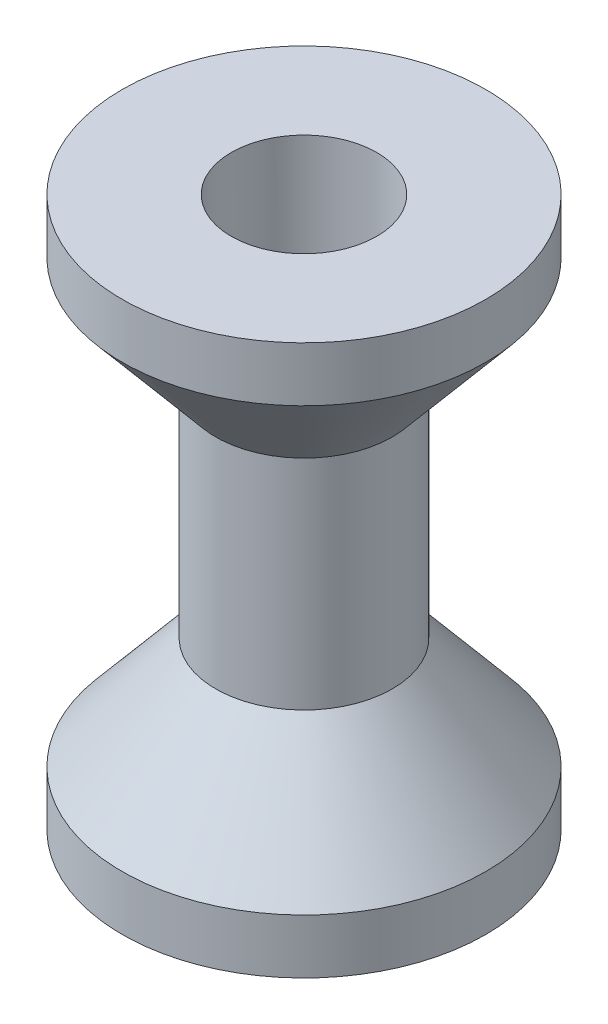
SolidWorks part; units mm, degrees
ref_plane "Alzado" through (0, 0, 0) normal (0, 0, 1) x (1, 0, 0)
ref_plane "Planta" through (0, 0, 0) normal (0, 1, 0) x (1, 0, 0)
ref_plane "Vista lateral" through (0, 0, 0) normal (1, 0, 0) x (0, 0, -1)
sketch "Croquis1" plane through (0, 0, 0) normal (0, 0, 1) x (1, 0, 0)
  line L0 (0, 6) -> (0, -6)
  line L1 (0, 0) -> (-12.7, 0) construction
  line L2 (0, 6) -> (-5.1423, 12.1284)
  line L3 (-5.1423, 12.1284) -> (-5.1423, 15.1284)
  line L4 (-5.1423, 15.1284) -> (4.8577, 15.1284)
  line L5 (0, -6) -> (-5.1423, -12.1284)
  line L6 (-5.1423, -12.1284) -> (-5.1423, -15.1284)
  line L7 (-5.1423, -15.1284) -> (4.8577, -15.1284)
  line L8 (4.8577, 15.1284) -> (4.8577, -15.1284)
  circle A3 centre (-12.7, 0) radius 12.7 construction
  point P4 (0, 0)
  dimension "D1" = 12.7
  dimension "D2" = 12
  dimension "D3" = 220
  dimension "D4" = 220
  dimension "D5" = 3
  dimension "D6" = 3
  dimension "D7" = 10
  dimension "D8" = 8
  dimension "D9" = 8
  dimension "D10" = 30.2567
  dimension "D11" = 4.8577
revolve "Revolución1" add sketch "Croquis1" angle 360 about L8
sketch "Croquis2" plane through (0, -15.1284, 0) normal (0, -1, 0) x (1, 0, 0)
  line L0 (4.8577, -10) -> (4.8577, 10) construction
  circle A0 centre (4.8577, 0) radius 10 construction
  circle A1 centre (4.8577, 0) radius 4
extrude "Cortar-Extruir1" cut sketch "Croquis2" against normal up to next
sketch "Croquis3" plane through (0, -15.1284, 0) normal (0, -1, 0) x (1, 0, 0)
  circle A0 centre (4.8577, 0) radius 5
extrude "Cortar-Extruir2" cut sketch "Croquis3" against normal blind 5
